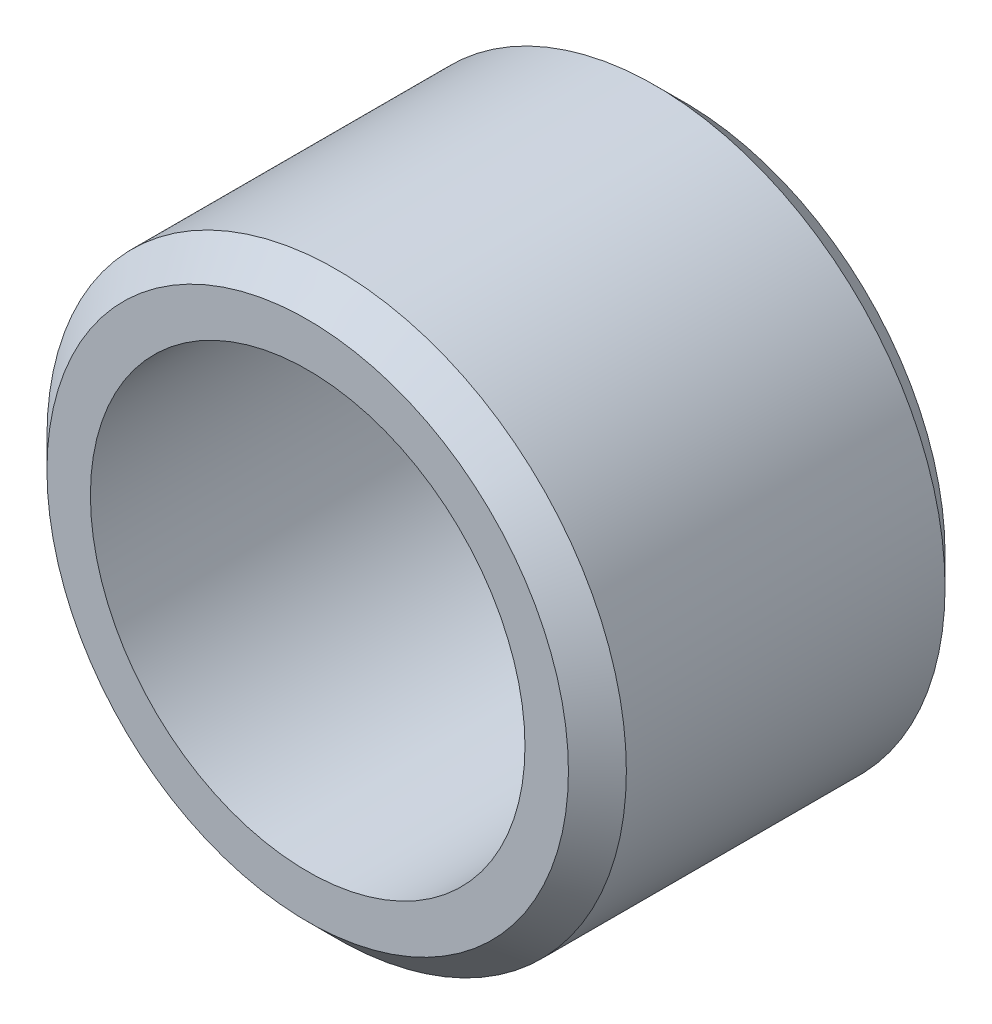
SolidWorks part; units mm, degrees
ref_plane "Front Plane" through (0, 0, 0) normal (0, 0, 1) x (1, 0, 0)
ref_plane "Top Plane" through (0, 0, 0) normal (0, 1, 0) x (1, 0, 0)
ref_plane "Right Plane" through (0, 0, 0) normal (1, 0, 0) x (0, 0, -1)
sketch "Sketch1" plane through (0, 0, 0) normal (0, 0, 1) x (1, 0, 0)
  circle A0 centre (0, 0) radius 7.5
  circle A1 centre (0, 0) radius 10
  dimension "D1" = 15
  dimension "D2" = 20
extrude "Boss-Extrude1" add sketch "Sketch1" along normal mid plane 13
chamfer "Chamfer1" distance 1 angle 45 2 edges at (10, 0, -6.5) (10, 0, 6.5)
